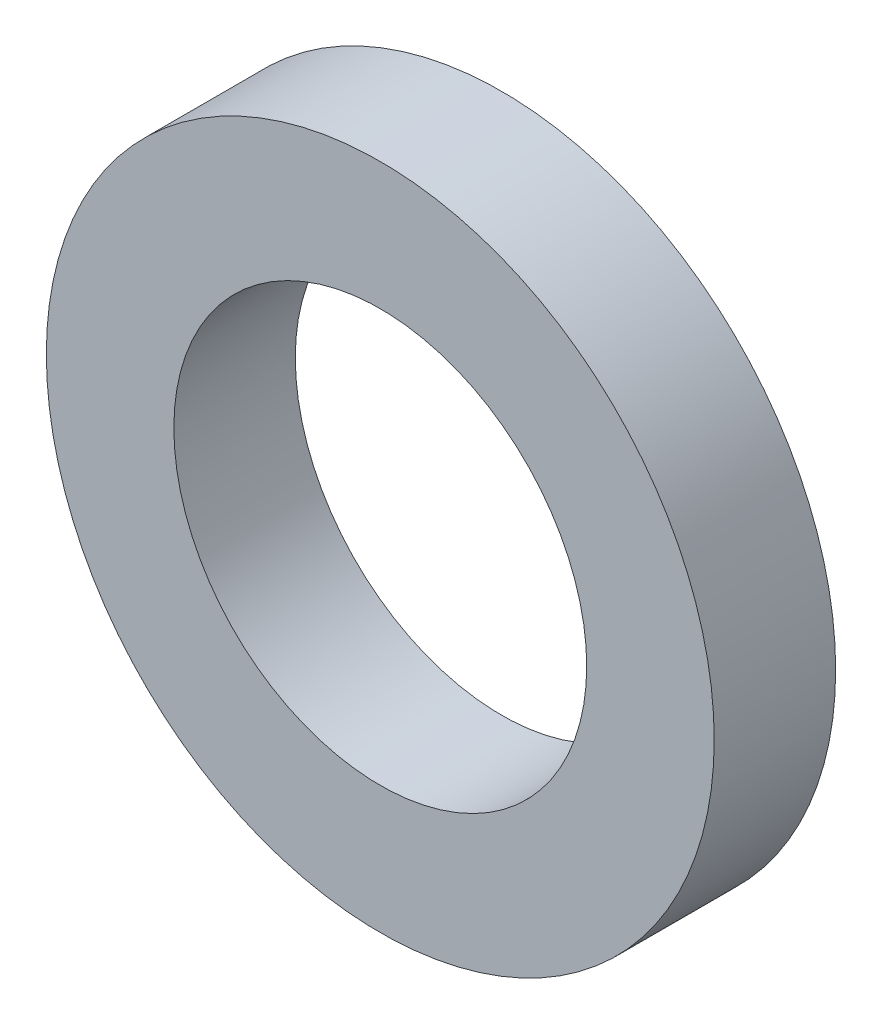
SolidWorks part; units mm, degrees
material "ABS"
ref_plane "前视基准面" through (0, 0, 0) normal (0, 0, 1) x (1, 0, 0)
ref_plane "上视基准面" through (0, 0, 0) normal (0, 1, 0) x (1, 0, 0)
ref_plane "右视基准面" through (0, 0, 0) normal (1, 0, 0) x (0, 0, -1)
sketch "草图1" plane through (0, 0, 0) normal (0, 0, 1) x (1, 0, 0)
  circle A0 centre (0, 0) radius 1.7
  circle A1 centre (0, 0) radius 2.75
  dimension "D1" = 5.5
  dimension "D2" = 3.4
extrude "凸台-拉伸1" add sketch "草图1" along normal blind 1
